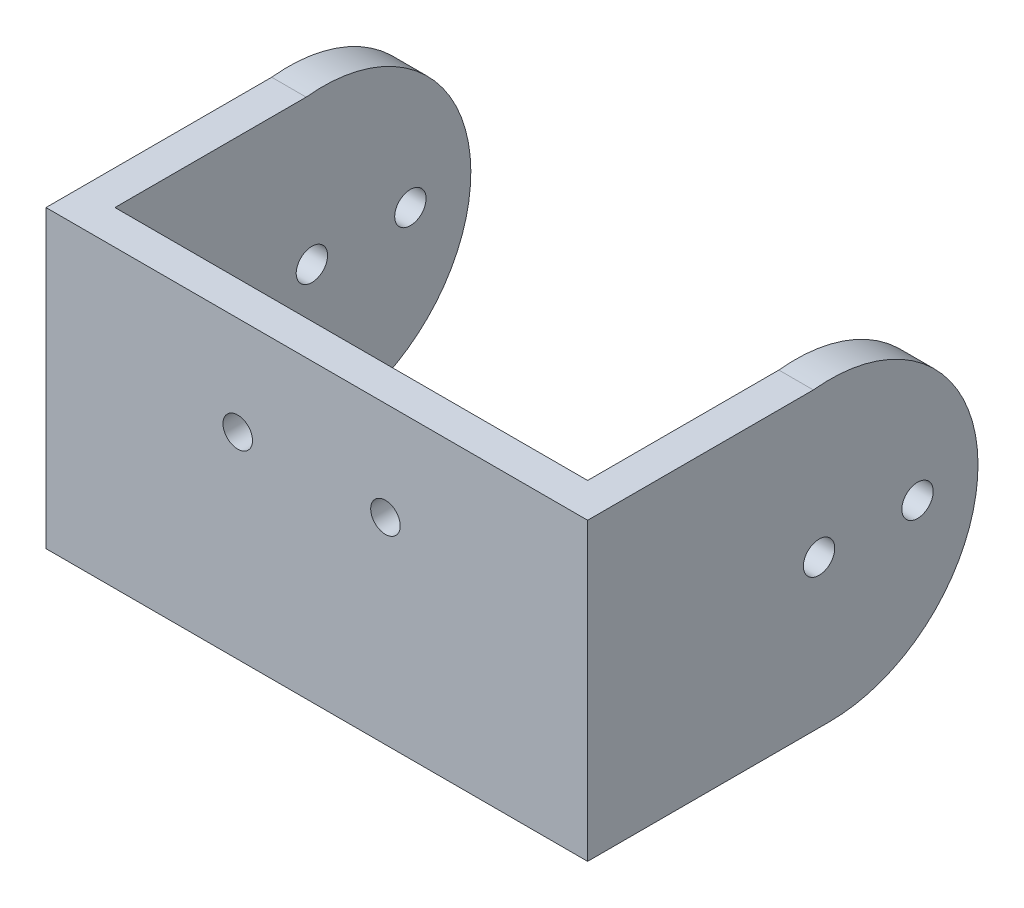
SolidWorks part; units mm, degrees
ref_plane "前视基准面" through (0, 0, 0) normal (0, 0, 1) x (1, 0, 0)
ref_plane "上视基准面" through (0, 0, 0) normal (0, 1, 0) x (1, 0, 0)
ref_plane "右视基准面" through (0, 0, 0) normal (1, 0, 0) x (0, 0, -1)
sketch "草图1" plane through (0, 0, 0) normal (0, 0, 1) x (1, 0, 0)
  line L1 (27.5, -15) -> (-27.5, -15)
  line L2 (27.5, -15) -> (27.5, 15)
  line L3 (27.5, 15) -> (-27.5, 15)
  line L4 (-27.5, -15) -> (-27.5, 15)
  point P0 (0, 0)
  dimension "D1" = 30
  dimension "D2" = 55
extrude "凸台-拉伸1" add sketch "草图1" along normal blind 3.5
ref_plane "基准面1" through (27.5, 0, 0) normal (1, 0, 0) x (0, 0, -1)
sketch "草图2" plane through (27.5, 0, 0) normal (1, 0, 0) x (0, 0, -1)
  line L0 (0, 15) -> (0, -15)
  line L1 (0, -15) -> (0, 15) construction
  line L2 (0, -15) -> (21, -15)
  line L4 (19.4198, 15) -> (0, 15)
  arc A0 (19.4198, 15) -> (21, -15) centre (21.093, 0.0465) cw
  circle A2 centre (20, 0) radius 1.5927
  circle A3 centre (20, 0) radius 10 construction
  circle A15 centre (30, 0) radius 1.5927
  dimension "D7" = 20
extrude "凸台-拉伸2" add sketch "草图2" against normal blind 3.5
mirror "镜向1" about plane through (0, 0, 0) normal (1, 0, 0) of "凸台-拉伸2"
sketch "草图3" plane through (0, 0, 3.5) normal (0, 0, 1) x (1, 0, 0)
  line L1 (-33.8419, 0) -> (30.3788, 0) construction
  line L2 (27.5, 15) -> (-27.5, 15) construction
  circle A2 centre (6.97, 4.99) radius 1.5
  circle A3 centre (-8.03, 4.99) radius 1.5
  point P17 (6.97, 6.2056)
  dimension "D1" = 15
  dimension "D2" = 3
  dimension "D3" = 3
  dimension "D5" = 10.01
extrude "切除-拉伸1" cut sketch "草图3" against normal blind 3.5
